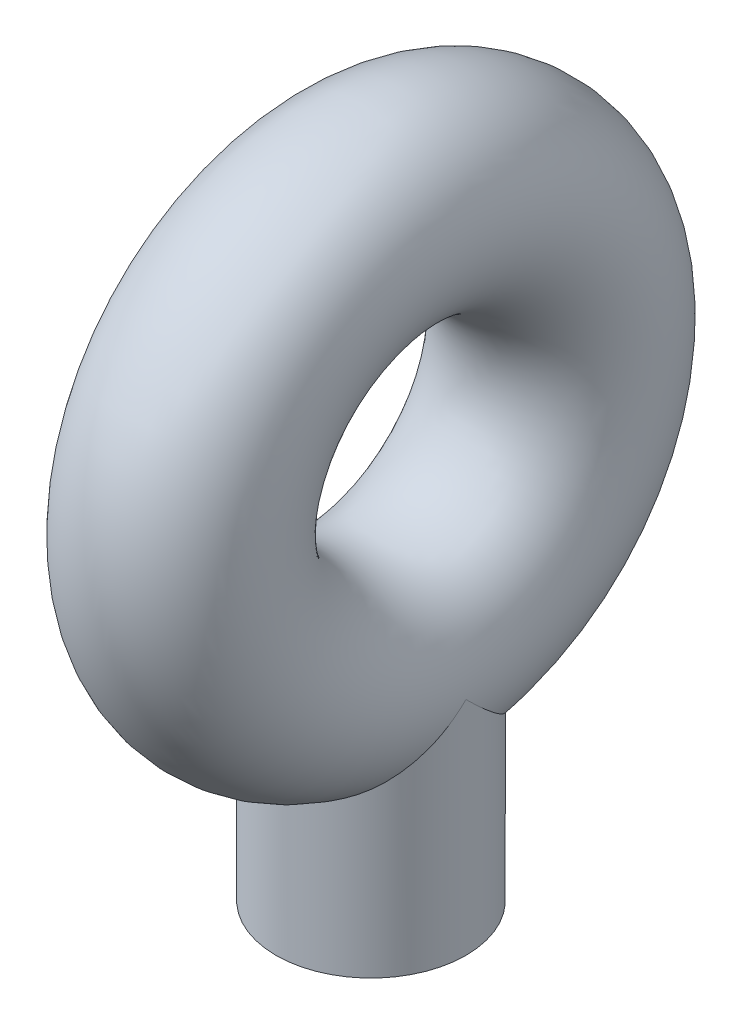
SolidWorks part; units mm, degrees
ref_plane "Front Plane" through (0, 0, 0) normal (0, 0, 1) x (1, 0, 0)
ref_plane "Top Plane" through (0, 0, 0) normal (0, 1, 0) x (1, 0, 0)
ref_plane "Right Plane" through (0, 0, 0) normal (1, 0, 0) x (0, 0, -1)
sketch "Sketch2" plane through (0, 0, 0) normal (0, 1, 0) x (1, 0, 0)
  circle A0 centre (0, 0) radius 1.5
  dimension "D1" = 3
extrude "Boss-Extrude1" add sketch "Sketch2" along normal blind 3.5
sketch "Sketch5" plane through (0, 0, 0) normal (1, 0, 0) x (0, 0, -1)
  line L0 (1.5, 3.5) -> (-1.5, 3.5) construction
  circle A1 centre (0, 6.5) radius 3
  dimension "D1" = 6
sketch "Sketch6" plane through (0, 0, 0) normal (0, 0, 1) x (1, 0, 0)
  line L0 (1.5, 3.5) -> (-1.5, 3.5) construction
  circle A0 centre (0, 3.5) radius 1.5
  dimension "D1" = 3
ref_axis "Axis1" through (0, 6.5, 0) along (1, 0, 0)
revolve "Revolve1" add sketch "Sketch6" angle 360 about axis through (0, 6.5, 0) along (1, 0, 0)
